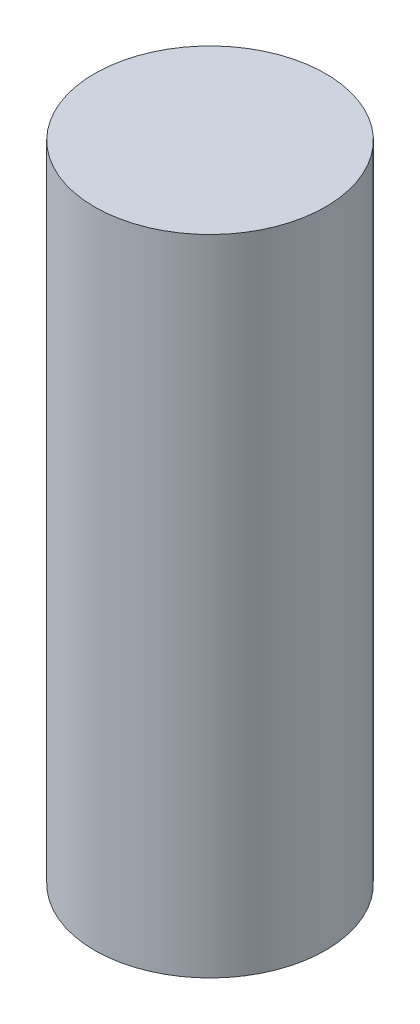
SolidWorks part; units mm, degrees
ref_plane "Front Plane" through (0, 0, 0) normal (0, 0, 1) x (1, 0, 0)
ref_plane "Top Plane" through (0, 0, 0) normal (0, 1, 0) x (1, 0, 0)
ref_plane "Right Plane" through (0, 0, 0) normal (1, 0, 0) x (0, 0, -1)
sketch "Sketch1" plane through (0, 0, 0) normal (0, 1, 0) x (1, 0, 0)
  circle A0 centre (0, 0) radius 31.125
  dimension "D1" = 62.25
extrude "Boss-Extrude1" add sketch "Sketch1" along normal blind 173.5
